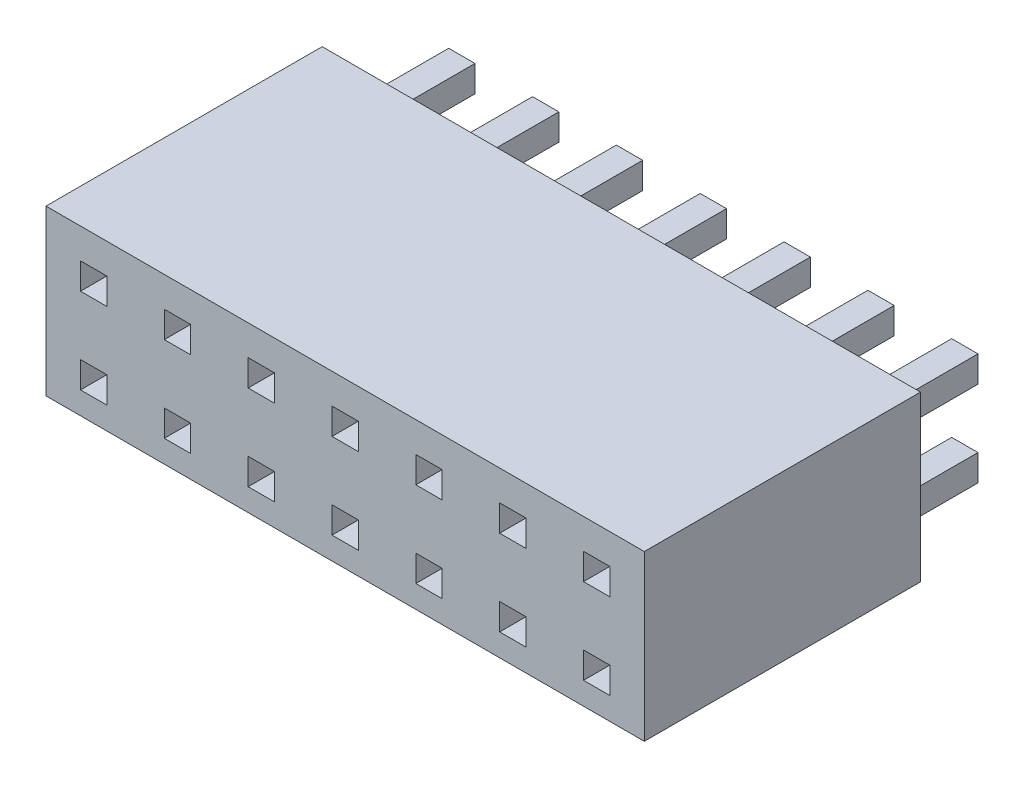
SolidWorks part; units mm, degrees
ref_plane "Přední rovina" through (0, 0, 0) normal (0, 0, 1) x (1, 0, 0)
ref_plane "Horní rovina" through (0, 0, 0) normal (0, 1, 0) x (1, 0, 0)
ref_plane "Pravá rovina" through (0, 0, 0) normal (1, 0, 0) x (0, 0, -1)
sketch "Skica1" plane through (0, 0, 0) normal (0, 0, 1) x (1, 0, 0)
  line L1 (0, 0) -> (18.2, 0)
  line L2 (0, 0) -> (0, 5)
  line L3 (0, 5) -> (18.2, 5)
  line L4 (18.2, 0) -> (18.2, 5)
  dimension "D1" = 18.2
  dimension "D2" = 5
extrude "Přidat vysunutím1" add sketch "Skica1" along normal blind 8.4
sketch "Skica3" plane through (0, 0, 8.4) normal (0, 0, 1) x (1, 0, 0)
  line L1 (1.05, 4.0827) -> (1.85, 4.0827)
  line L2 (1.05, 4.0827) -> (1.05, 3.2827)
  line L3 (1.05, 3.2827) -> (1.85, 3.2827)
  line L4 (1.85, 4.0827) -> (1.85, 3.2827)
  line L5 (1.05, 1.4827) -> (1.85, 1.4827)
  line L6 (1.05, 1.4827) -> (1.05, 0.6827)
  line L7 (1.05, 0.6827) -> (1.85, 0.6827)
  line L8 (1.85, 1.4827) -> (1.85, 0.6827)
  line L9 (6.15, 4.0827) -> (6.95, 4.0827)
  line L10 (0, 5) -> (0, 0) construction
  line L12 (3.6, 4.0827) -> (4.4, 4.0827)
  line L13 (3.6, 4.0827) -> (3.6, 3.2827)
  line L14 (3.6, 3.2827) -> (4.4, 3.2827)
  line L15 (4.4, 4.0827) -> (4.4, 3.2827)
  line L16 (3.6, 1.4827) -> (4.4, 1.4827)
  line L17 (3.6, 1.4827) -> (3.6, 0.6827)
  line L18 (3.6, 0.6827) -> (4.4, 0.6827)
  line L19 (4.4, 1.4827) -> (4.4, 0.6827)
  line L20 (6.15, 4.0827) -> (6.15, 3.2827)
  line L21 (6.15, 3.2827) -> (6.95, 3.2827)
  line L22 (6.95, 4.0827) -> (6.95, 3.2827)
  line L23 (6.15, 1.4827) -> (6.95, 1.4827)
  line L24 (6.15, 1.4827) -> (6.15, 0.6827)
  line L25 (6.15, 0.6827) -> (6.95, 0.6827)
  line L26 (6.95, 1.4827) -> (6.95, 0.6827)
  line L27 (8.7, 4.0827) -> (9.5, 4.0827)
  line L28 (8.7, 4.0827) -> (8.7, 3.2827)
  line L29 (8.7, 3.2827) -> (9.5, 3.2827)
  line L30 (9.5, 4.0827) -> (9.5, 3.2827)
  line L31 (8.7, 1.4827) -> (9.5, 1.4827)
  line L32 (8.7, 1.4827) -> (8.7, 0.6827)
  line L33 (8.7, 0.6827) -> (9.5, 0.6827)
  line L34 (9.5, 1.4827) -> (9.5, 0.6827)
  line L35 (11.25, 4.0827) -> (12.05, 4.0827)
  line L36 (11.25, 4.0827) -> (11.25, 3.2827)
  line L37 (11.25, 3.2827) -> (12.05, 3.2827)
  line L38 (12.05, 4.0827) -> (12.05, 3.2827)
  line L39 (11.25, 1.4827) -> (12.05, 1.4827)
  line L40 (11.25, 1.4827) -> (11.25, 0.6827)
  line L41 (11.25, 0.6827) -> (12.05, 0.6827)
  line L42 (12.05, 1.4827) -> (12.05, 0.6827)
  line L43 (13.8, 4.0827) -> (14.6, 4.0827)
  line L44 (13.8, 4.0827) -> (13.8, 3.2827)
  line L45 (13.8, 3.2827) -> (14.6, 3.2827)
  line L46 (14.6, 4.0827) -> (14.6, 3.2827)
  line L47 (13.8, 1.4827) -> (14.6, 1.4827)
  line L48 (13.8, 1.4827) -> (13.8, 0.6827)
  line L49 (13.8, 0.6827) -> (14.6, 0.6827)
  line L50 (14.6, 1.4827) -> (14.6, 0.6827)
  line L51 (16.35, 4.0827) -> (17.15, 4.0827)
  line L52 (16.35, 4.0827) -> (16.35, 3.2827)
  line L53 (16.35, 3.2827) -> (17.15, 3.2827)
  line L54 (17.15, 4.0827) -> (17.15, 3.2827)
  line L55 (16.35, 1.4827) -> (17.15, 1.4827)
  line L56 (16.35, 1.4827) -> (16.35, 0.6827)
  line L57 (16.35, 0.6827) -> (17.15, 0.6827)
  line L58 (17.15, 1.4827) -> (17.15, 0.6827)
  dimension "D2" = 0.8
  dimension "D4" = 1.8
  dimension "D5" = 1.8
  dimension "D6" = 1.8
  dimension "D7" = 1.8
  dimension "D8" = 1.8
  dimension "D9" = 1.8
  dimension "D10" = 1.8
  dimension "D11" = 1.05
  dimension "D13" = 1.75
  dimension "D14" = 1.75
  dimension "D15" = 1.75
  dimension "D16" = 1.75
  dimension "D17" = 1.75
  dimension "D18" = 1.75
  dimension "D19" = 1.75
  dimension "D20" = 1.75
  dimension "D21" = 1.75
  dimension "D22" = 1.75
  dimension "D23" = 1.75
  dimension "D24" = 1.75
  dimension "D25" = 0.8
  dimension "D26" = 0.8
  dimension "D27" = 0.8
  dimension "D28" = 0.8
  dimension "D29" = 0.8
  dimension "D30" = 0.8
  dimension "D31" = 0.8
  dimension "D32" = 0.8
  dimension "D33" = 0.8
  dimension "D34" = 0.8
  dimension "D35" = 0.8
  dimension "D36" = 0.8
extrude "Odebrat vysunutím1" cut sketch "Skica3" against normal blind 6
ref_plane "Rovina1" through (9.1, 0, 0) normal (1, 0, 0) x (0, 0, -1)
ref_plane "Rovina2" through (17.15, 0.6827, 2.4) normal (1, 0, 0) x (0, 0, -1)
sketch "Skica6" plane through (0, 0, 0) normal (0, 0, -1) x (-1, 0, 0)
  line L0 (-1.85, 4.0827) -> (-1.05, 4.0827) construction
  line L1 (-1.85, 3.2827) -> (-1.85, 4.0827) construction
  line L2 (-4.4, 3.2827) -> (-4.4, 4.0827) construction
  line L3 (-4.4, 4.0827) -> (-3.6, 4.0827) construction
  line L4 (-6.95, 4.0827) -> (-6.15, 4.0827) construction
  line L5 (-6.95, 3.2827) -> (-6.95, 4.0827) construction
  line L6 (-9.5, 4.0827) -> (-8.7, 4.0827) construction
  line L7 (-9.5, 3.2827) -> (-9.5, 4.0827) construction
  line L8 (-12.05, 4.0827) -> (-11.25, 4.0827) construction
  line L9 (-12.05, 3.2827) -> (-12.05, 4.0827) construction
  line L10 (-14.6, 3.2827) -> (-14.6, 4.0827) construction
  line L11 (-14.6, 4.0827) -> (-13.8, 4.0827) construction
  line L12 (-16.35, 4.0827) -> (-16.35, 3.2827) construction
  line L13 (-16.35, 3.2827) -> (-17.15, 3.2827) construction
  line L14 (-17.15, 3.2827) -> (-17.15, 4.0827) construction
  line L15 (-17.15, 4.0827) -> (-16.35, 4.0827) construction
  line L16 (-13.8, 4.0827) -> (-13.8, 3.2827) construction
  line L17 (-13.8, 3.2827) -> (-14.6, 3.2827) construction
  line L18 (-11.25, 4.0827) -> (-11.25, 3.2827) construction
  line L19 (-11.25, 3.2827) -> (-12.05, 3.2827) construction
  line L20 (-8.7, 4.0827) -> (-8.7, 3.2827) construction
  line L21 (-8.7, 3.2827) -> (-9.5, 3.2827) construction
  line L22 (-6.15, 4.0827) -> (-6.15, 3.2827) construction
  line L23 (-6.15, 3.2827) -> (-6.95, 3.2827) construction
  line L24 (-3.6, 4.0827) -> (-3.6, 3.2827) construction
  line L25 (-3.6, 3.2827) -> (-4.4, 3.2827) construction
  line L26 (-1.05, 4.0827) -> (-1.05, 3.2827) construction
  line L27 (-1.05, 3.2827) -> (-1.85, 3.2827) construction
  line L28 (-1.05, 1.4827) -> (-1.05, 0.6827) construction
  line L29 (-1.05, 0.6827) -> (-1.85, 0.6827) construction
  line L30 (-3.6, 1.4827) -> (-3.6, 0.6827) construction
  line L31 (-3.6, 0.6827) -> (-4.4, 0.6827) construction
  line L32 (-6.15, 1.4827) -> (-6.15, 0.6827) construction
  line L33 (-6.15, 0.6827) -> (-6.95, 0.6827) construction
  line L34 (-1.85, 1.4827) -> (-1.05, 1.4827) construction
  line L35 (-1.85, 0.6827) -> (-1.85, 1.4827) construction
  line L36 (-4.4, 0.6827) -> (-4.4, 1.4827) construction
  line L37 (-4.4, 1.4827) -> (-3.6, 1.4827) construction
  line L38 (-6.95, 0.6827) -> (-6.95, 1.4827) construction
  line L39 (-6.95, 1.4827) -> (-6.15, 1.4827) construction
  line L40 (-9.5, 1.4827) -> (-8.7, 1.4827) construction
  line L41 (-9.5, 0.6827) -> (-9.5, 1.4827) construction
  line L42 (-8.7, 0.6827) -> (-9.5, 0.6827) construction
  line L43 (-8.7, 1.4827) -> (-8.7, 0.6827) construction
  line L44 (-11.25, 1.4827) -> (-11.25, 0.6827) construction
  line L45 (-11.25, 0.6827) -> (-12.05, 0.6827) construction
  line L46 (-12.05, 1.4827) -> (-11.25, 1.4827) construction
  line L47 (-12.05, 0.6827) -> (-12.05, 1.4827) construction
  line L48 (-14.6, 1.4827) -> (-13.8, 1.4827) construction
  line L49 (-14.6, 0.6827) -> (-14.6, 1.4827) construction
  line L50 (-13.8, 1.4827) -> (-13.8, 0.6827) construction
  line L51 (-13.8, 0.6827) -> (-14.6, 0.6827) construction
  line L52 (-17.15, 1.4827) -> (-16.35, 1.4827) construction
  line L53 (-16.35, 1.4827) -> (-16.35, 0.6827) construction
  line L54 (-17.15, 0.6827) -> (-17.15, 1.4827) construction
  line L55 (-16.35, 0.6827) -> (-17.15, 0.6827) construction
  line L56 (-1.85, 4.0827) -> (-1.05, 4.0827)
  line L57 (-1.85, 3.2827) -> (-1.85, 4.0827)
  line L58 (-4.4, 3.2827) -> (-4.4, 4.0827)
  line L59 (-4.4, 4.0827) -> (-3.6, 4.0827)
  line L60 (-6.95, 4.0827) -> (-6.15, 4.0827)
  line L61 (-6.95, 3.2827) -> (-6.95, 4.0827)
  line L62 (-9.5, 4.0827) -> (-8.7, 4.0827)
  line L63 (-9.5, 3.2827) -> (-9.5, 4.0827)
  line L64 (-12.05, 4.0827) -> (-11.25, 4.0827)
  line L65 (-12.05, 3.2827) -> (-12.05, 4.0827)
  line L66 (-14.6, 3.2827) -> (-14.6, 4.0827)
  line L67 (-14.6, 4.0827) -> (-13.8, 4.0827)
  line L68 (-16.35, 4.0827) -> (-16.35, 3.2827)
  line L69 (-16.35, 3.2827) -> (-17.15, 3.2827)
  line L70 (-17.15, 3.2827) -> (-17.15, 4.0827)
  line L71 (-17.15, 4.0827) -> (-16.35, 4.0827)
  line L72 (-13.8, 4.0827) -> (-13.8, 3.2827)
  line L73 (-13.8, 3.2827) -> (-14.6, 3.2827)
  line L74 (-11.25, 4.0827) -> (-11.25, 3.2827)
  line L75 (-11.25, 3.2827) -> (-12.05, 3.2827)
  line L76 (-8.7, 4.0827) -> (-8.7, 3.2827)
  line L77 (-8.7, 3.2827) -> (-9.5, 3.2827)
  line L78 (-6.15, 4.0827) -> (-6.15, 3.2827)
  line L79 (-6.15, 3.2827) -> (-6.95, 3.2827)
  line L80 (-3.6, 4.0827) -> (-3.6, 3.2827)
  line L81 (-3.6, 3.2827) -> (-4.4, 3.2827)
  line L82 (-1.05, 4.0827) -> (-1.05, 3.2827)
  line L83 (-1.05, 3.2827) -> (-1.85, 3.2827)
  line L84 (-1.05, 1.4827) -> (-1.05, 0.6827)
  line L85 (-1.05, 0.6827) -> (-1.85, 0.6827)
  line L86 (-3.6, 1.4827) -> (-3.6, 0.6827)
  line L87 (-3.6, 0.6827) -> (-4.4, 0.6827)
  line L88 (-6.15, 1.4827) -> (-6.15, 0.6827)
  line L89 (-6.15, 0.6827) -> (-6.95, 0.6827)
  line L90 (-1.85, 1.4827) -> (-1.05, 1.4827)
  line L91 (-1.85, 0.6827) -> (-1.85, 1.4827)
  line L92 (-4.4, 0.6827) -> (-4.4, 1.4827)
  line L93 (-4.4, 1.4827) -> (-3.6, 1.4827)
  line L94 (-6.95, 0.6827) -> (-6.95, 1.4827)
  line L95 (-6.95, 1.4827) -> (-6.15, 1.4827)
  line L96 (-9.5, 1.4827) -> (-8.7, 1.4827)
  line L97 (-9.5, 0.6827) -> (-9.5, 1.4827)
  line L98 (-8.7, 0.6827) -> (-9.5, 0.6827)
  line L99 (-8.7, 1.4827) -> (-8.7, 0.6827)
  line L100 (-11.25, 1.4827) -> (-11.25, 0.6827)
  line L101 (-11.25, 0.6827) -> (-12.05, 0.6827)
  line L102 (-12.05, 1.4827) -> (-11.25, 1.4827)
  line L103 (-12.05, 0.6827) -> (-12.05, 1.4827)
  line L104 (-14.6, 1.4827) -> (-13.8, 1.4827)
  line L105 (-14.6, 0.6827) -> (-14.6, 1.4827)
  line L106 (-13.8, 1.4827) -> (-13.8, 0.6827)
  line L107 (-13.8, 0.6827) -> (-14.6, 0.6827)
  line L108 (-17.15, 1.4827) -> (-16.35, 1.4827)
  line L109 (-16.35, 1.4827) -> (-16.35, 0.6827)
  line L110 (-17.15, 0.6827) -> (-17.15, 1.4827)
  line L111 (-16.35, 0.6827) -> (-17.15, 0.6827)
extrude "Přidat vysunutím2" add sketch "Skica6" along normal blind 2.8
